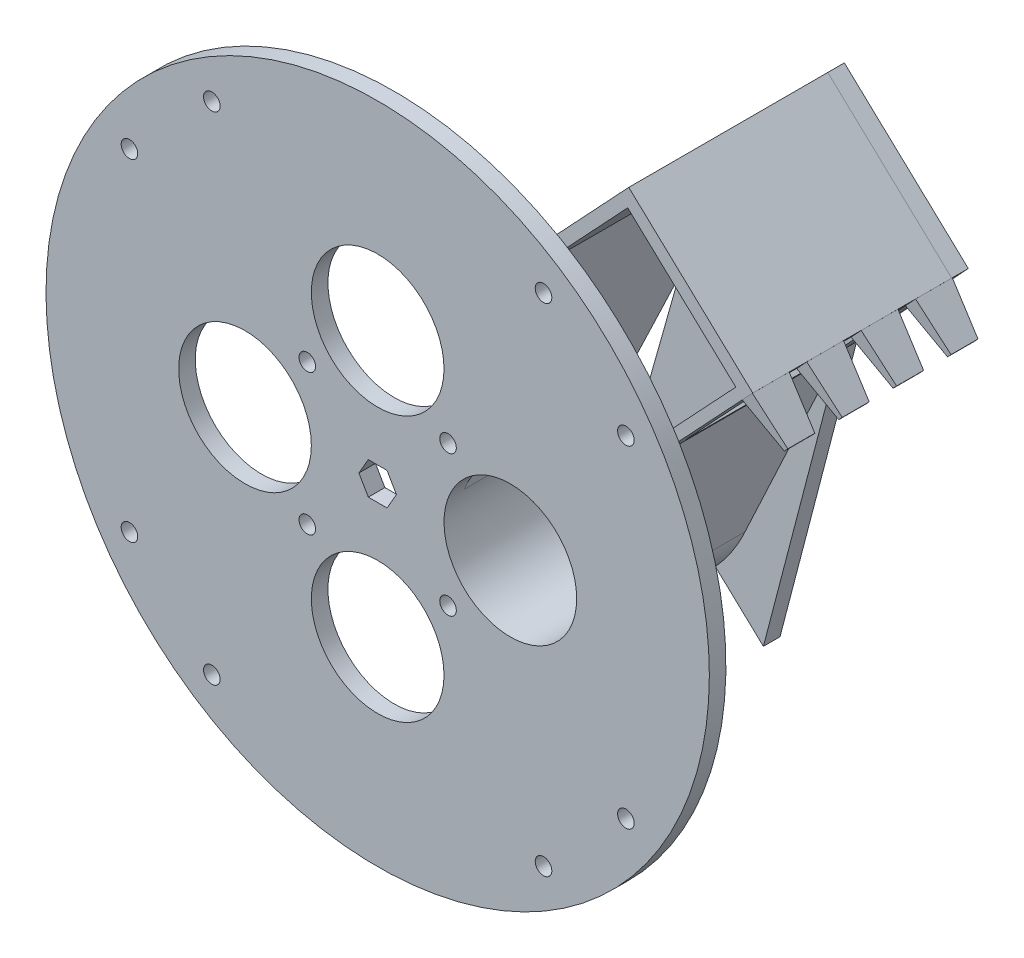
SolidWorks part; units mm, degrees
ref_plane "Front Plane" through (0, 0, 0) normal (0, 0, 1) x (1, 0, 0)
ref_plane "Top Plane" through (0, 0, 0) normal (0, 1, 0) x (1, 0, 0)
ref_plane "Right Plane" through (0, 0, 0) normal (1, 0, 0) x (0, 0, -1)
sketch "Sketch1" plane through (0, 0, 0) normal (0, 0, 1) x (1, 0, 0)
  line L1 (7.1857, 0) -> (3.5929, 6.223)
  line L2 (3.5929, 6.223) -> (-3.5929, 6.223)
  line L3 (-3.5929, 6.223) -> (-7.1857, 0)
  line L4 (-7.1857, 0) -> (-3.5929, -6.223)
  line L5 (-3.5929, -6.223) -> (3.5929, -6.223)
  line L6 (3.5929, -6.223) -> (7.1857, 0)
  circle A0 centre (0, 0) radius 127
  circle A2 centre (0, 50.8) radius 25.4
  circle A3 centre (50.8, 0) radius 25.4
  circle A4 centre (0, -50.8) radius 25.4
  circle A5 centre (-50.8, 0) radius 25.4
  circle A7 centre (0, 0) radius 203.2 construction
  circle A8 centre (0, 0) radius 6.223 construction
  point P14 (0, 0)
  dimension "D1" = 254
  dimension "D2" = 25.4
  dimension "D3" = 4
  dimension "2" = 50.8
  dimension "D4" = 12.446
  dimension "D5" = 406.4
extrude "Boss-Extrude1" add sketch "Sketch1" along normal blind 6.35
sketch "Sketch3" plane through (0, 0, 0) normal (0, 0, -1) x (-1, 0, 0)
  line L0 (-26.9408, -26.9408) -> (26.9408, 26.9408) construction
  line L1 (-26.9408, 26.9408) -> (26.9408, -26.9408) construction
  line L2 (-63.5, 95.0381) -> (0, 0) construction
  line L3 (0, 0) -> (63.5, 95.0381) construction
  circle A0 centre (-26.9408, 26.9408) radius 3.175
  circle A1 centre (26.9408, 26.9408) radius 3.175
  circle A2 centre (26.9408, -26.9408) radius 3.175
  circle A3 centre (-26.9408, -26.9408) radius 3.175
  circle A4 centre (-63.5, 95.0381) radius 3.175
  circle A5 centre (63.5, 95.0381) radius 3.175
  circle A6 centre (95.0381, 63.5) radius 3.175
  circle A7 centre (95.0381, -63.5) radius 3.175
  circle A8 centre (63.5, -95.0381) radius 3.175
  circle A9 centre (-63.5, -95.0381) radius 3.175
  circle A10 centre (-95.0381, -63.5) radius 3.175
  circle A11 centre (-95.0381, 63.5) radius 3.175
  point P29 (0, 0)
  dimension "D1" = 6.35
  dimension "D2" = 76.2
  dimension "D3" = 127
  dimension "D4" = 114.3
  dimension "D5" = 4
extrude "Cut-Extrude1" cut sketch "Sketch3" against normal blind 6.35
surface "Surface-Plane1"
sketch "Sketch4" plane through (0, 0, 0) normal (0, 0, -1) x (-1, 0, 0)
  line L0 (-61.255, 92.793) -> (-92.7297, 61.3201) construction
  line L1 (-63.5, 95.0381) -> (-95.3816, 63.1565) construction
  line L2 (-63.5, 95.0381) -> (-55.6363, 102.9018) construction
  line L3 (-95.3816, 63.1565) -> (-101.5673, 56.9708) construction
  line L4 (-101.5673, 56.9708) -> (-94.5022, 49.9057) construction
  line L5 (-94.5022, 49.9057) -> (-47.0312, 94.3686) construction
  line L6 (-47.0312, 94.3686) -> (-89.7897, 140.0199) construction
  line L7 (-89.7897, 140.0199) -> (-137.2607, 95.557) construction
  line L8 (-137.2607, 95.557) -> (-101.5673, 56.9708) construction
  line L9 (-47.0312, 94.3686) -> (-22.9112, 8.8206) construction
  line L10 (-15.8012, -16.3967) -> (-65.1502, -62.6185) construction
  line L11 (-79.1851, -7.0622) -> (-94.5022, 49.9057) construction
  line L12 (-22.9112, 8.8206) -> (-47.0312, 94.3686)
  line L13 (-47.0312, 94.3686) -> (-89.7897, 140.0199)
  line L14 (-89.7897, 140.0199) -> (-137.2607, 95.557)
  line L15 (-137.2607, 95.557) -> (-94.5022, 49.9057)
  line L16 (-94.5022, 49.9057) -> (-79.1851, -7.0622)
  line L18 (-75.0781, -7.4654) -> (-91.6903, 52.5394)
  line L19 (-91.6903, 52.5394) -> (-130.775, 94.2684)
  line L20 (-26.858, 8.4817) -> (-50.3033, 91.3037)
  line L21 (-50.3033, 91.3037) -> (-89.3881, 133.0328)
  line L22 (-89.3881, 133.0328) -> (-130.775, 94.2684)
  circle A0 centre (-63.5, 95.0381) radius 3.175 construction
  circle A1 centre (-95.0381, 63.5) radius 3.175 construction
  circle A2 centre (-50.8, 0) radius 25.4 construction
  arc A3 (-75.4608, -6.0832) -> (-26.858, 8.4817) centre (-50.8, 0) ccw
  arc A4 (-79.1851, -7.0622) -> (-22.9112, 8.8206) centre (-50.8, 0) ccw
  point P31 (0, 0)
  point P32 (-22.7548, 8.6577)
extrude "Boss-Extrude3" add sketch "Sketch4" along normal blind 76.2
ref_plane "Plane1" through (0, 0, -76.2) normal (0, 0, -1) x (-1, 0, 0)
sketch "Sketch8" plane through (25.4404, -23.8283, 0) normal (0.7299, -0.6836, 0) x (0, 0, -1)
  line L0 (0, 163.5746) -> (76.2, 101.0259) construction
  line L1 (76.2, -63.6411) -> (76.2, 63.6411) construction
  line L2 (76.2, 101.0259) -> (0, 101.0259) construction
  line L3 (38.1, 101.0259) -> (38.1, 163.5746) construction
  line L4 (76.2, 163.5746) -> (0, 163.5746) construction
  line L5 (76.2, 163.5746) -> (0, 101.0259) construction
  line L7 (12.7, 157.7002) -> (63.5, 157.7002)
  line L8 (12.7, 157.7002) -> (12.7, 106.9002)
  line L9 (12.7, 106.9002) -> (63.5, 106.9002)
  line L10 (63.5, 157.7002) -> (63.5, 106.9002)
  line L11 (12.7, 157.7002) -> (63.5, 106.9002) construction
  line L12 (12.7, 106.9002) -> (63.5, 157.7002) construction
  point P14 (38.1, 132.3002)
  dimension "D1" = 50.8
  dimension "D2" = 50.8
extrude "Cut-Extrude2" cut sketch "Sketch8" against normal blind 6.35
sketch "Sketch6" plane through (0, 0, -76.2) normal (0, 0, -1) x (-1, 0, 0)
  line L6 (-47.0312, 94.3686) -> (-89.7897, 140.0199) construction
  line L7 (-89.7897, 140.0199) -> (-137.2607, 95.557) construction
  line L9 (-47.0312, 94.3686) -> (-15.8012, -16.3967) construction
  line L10 (-15.8012, -16.3967) -> (-65.1502, -62.6185) construction
  line L11 (-65.1502, -62.6185) -> (-94.5022, 49.9057) construction
  line L12 (-15.8012, -16.3967) -> (-47.0312, 94.3686)
  line L13 (-47.0312, 94.3686) -> (-89.7897, 140.0199)
  line L14 (-89.7897, 140.0199) -> (-137.2607, 95.557)
  line L15 (-137.2607, 95.557) -> (-94.5022, 49.9057)
  line L16 (-94.5022, 49.9057) -> (-65.1502, -62.6185)
  line L17 (-65.1502, -62.6185) -> (-15.8012, -16.3967)
extrude "Boss-Extrude4" add sketch "Sketch6" along normal blind 6.35 separate body
ref_plane "Plane2" through (75.6175, -20.3313, 0) normal (0.9657, -0.2596, 0) x (0, 0, -1)
sketch "Sketch10" plane through (75.6175, -20.3313, 0) normal (0.9657, -0.2596, 0) x (0, 0, -1)
  line L0 (44.4538, -16.0603) -> (76.2, 72.7315) construction
  point P2 (76.1227, 72.7125)
  point P3 (34.2564, -35.5849)
  point P4 (77.0196, 72.6402)
  point P6 (31.6202, -19.7099)
  point P7 (29.2776, -11.0271)
  point P8 (20.2368, -20.0627)
  point P9 (44.4538, -16.0603)
ref_plane "Plane3" through (0, 0, -76.2) normal (0, 0, -1) x (-1, 0, 0)
ref_plane "Plane4" through (25.4404, -23.8283, 0) normal (0.7299, -0.6836, 0) x (0, 0, -1)
sketch "Sketch12" plane through (25.4404, -23.8283, 0) normal (0.7299, -0.6836, 0) x (0, 0, -1)
  line L0 (63.5, 157.7002) -> (12.7, 157.7002) construction
  line L1 (0, 163.3763) -> (14.0762, 163.3763)
  line L2 (0, 163.3763) -> (0, 157.7002)
  line L3 (0, 157.7002) -> (14.0762, 157.7002)
  line L4 (14.0762, 163.3763) -> (14.0762, 157.7002)
  line L5 (20.828, 163.3763) -> (20.828, 157.7002)
  line L6 (20.828, 163.3763) -> (34.9042, 163.3763)
  line L7 (34.9042, 163.3763) -> (34.9042, 157.7002)
  line L8 (20.828, 157.7002) -> (34.9042, 157.7002)
  line L9 (41.656, 163.3763) -> (41.656, 157.7002)
  line L10 (41.656, 163.3763) -> (55.7322, 163.3763)
  line L11 (55.7322, 163.3763) -> (55.7322, 157.7002)
  line L12 (41.656, 157.7002) -> (55.7322, 157.7002)
  line L13 (62.484, 163.3763) -> (62.484, 157.7002)
  line L14 (62.484, 163.3763) -> (76.5602, 163.3763)
  line L15 (76.5602, 163.3763) -> (76.5602, 157.7002)
  line L16 (62.484, 157.7002) -> (76.5602, 157.7002)
  line L17 (0, 163.3763) -> (20.828, 163.3763) construction
  dimension "D2" = 20.828
  dimension "D1" = 4
extrude "Boss-Extrude5" add sketch "Sketch12" along normal blind 17.78 draft 6
ref_plane "Plane5" through (75.6175, -20.3313, 0) normal (0.9657, -0.2596, 0) x (0, 0, -1)
sketch "Sketch13" plane through (75.6175, -20.3313, 0) normal (0.9657, -0.2596, 0) x (0, 0, -1)
  line L0 (0, 13.7404) -> (-6.35, 13.7404) construction
  line L1 (-6.35, 13.7404) -> (44.4538, 13.7404) construction
  line L3 (76.2, 13.7404) -> (0, 13.7404) construction
  line L4 (-6.35, 127) -> (-6.35, -127) construction
  line L5 (44.4538, 13.7404) -> (44.4538, -16.0603) construction
  line L6 (0, -16.0603) -> (76.2, -16.0603) construction
sketch "Sketch14" plane through (0, 0, -76.2) normal (0, 0, -1) x (-1, 0, 0)
  line L0 (-50.8, 0) -> (-43.5087, -24.331) construction
  line L1 (-43.5087, -24.331) -> (-72.2281, -32.9374) construction
  line L2 (-71.4474, -35.8408) -> (-94.5022, 49.9057) construction
  arc A0 (-75.4608, -6.0832) -> (-26.858, 8.4817) centre (-50.8, 0) ccw construction
ref_plane "Plane6" through (-4.2891, -15.2126, -44.2042) normal (0.0914, 0.3241, 0.9416) x (0.2445, 0.9093, -0.3367)
sketch "Sketch16" plane through (-4.2891, -15.2126, -44.2042) normal (0.0914, 0.3241, 0.9416) x (0.2445, 0.9093, -0.3367)
  line L1 (-18.1114, -16.2623) -> (119.5214, -16.2623)
  line L2 (-18.1114, -16.2623) -> (-18.1114, -102.9517)
  line L3 (-18.1114, -102.9517) -> (119.5214, -102.9517)
  line L4 (119.5214, -16.2623) -> (119.5214, -102.9517)
extrude "Cut-Extrude4" cut sketch "Sketch16" against normal blind 38.1 contours L1 L4 L3 L2
